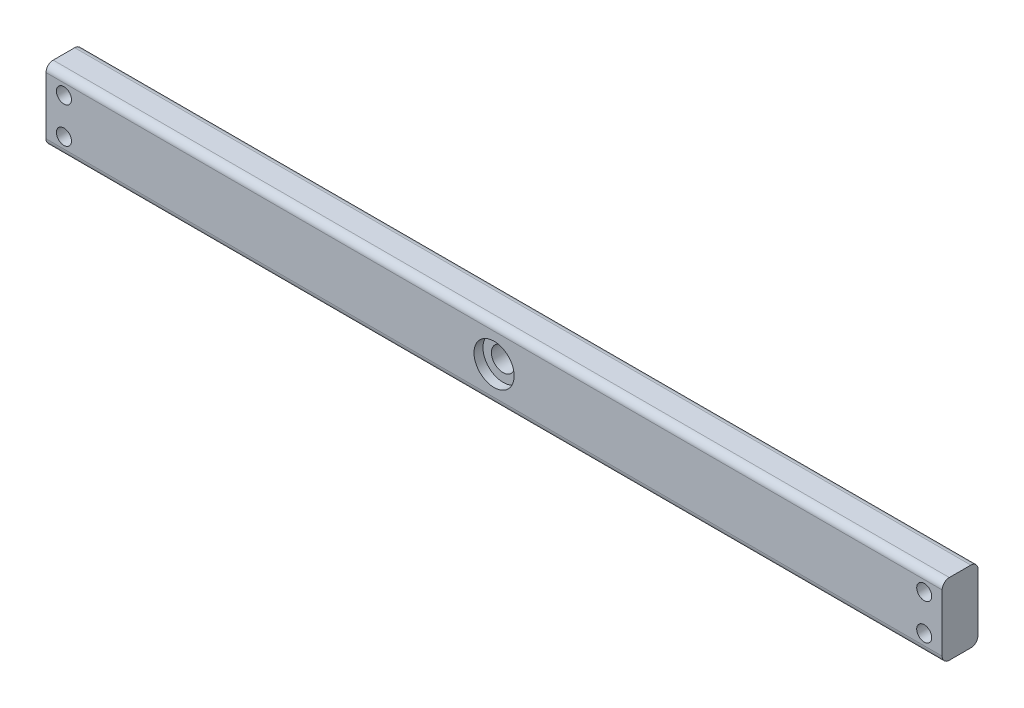
SolidWorks part; units mm, degrees
ref_plane "前视基准面" through (0, 0, 0) normal (0, 0, 1) x (1, 0, 0)
ref_plane "上视基准面" through (0, 0, 0) normal (0, 1, 0) x (1, 0, 0)
ref_plane "右视基准面" through (0, 0, 0) normal (1, 0, 0) x (0, 0, -1)
other "Configuration Table"
sketch "草图1" plane through (0, 0, 0) normal (0, 0, 1) x (1, 0, 0)
  line L1 (-125, 10) -> (125, 10)
  line L2 (-125, 10) -> (-125, -10)
  line L3 (-125, -10) -> (125, -10)
  line L4 (125, 10) -> (125, -10)
  line L5 (-125, 10) -> (125, -10) construction
  line L6 (-125, -10) -> (125, 10) construction
  circle A0 centre (0, 0) radius 3.25
  point P0 (0, 0)
  dimension "D1" = 6.5
  dimension "D2" = 250
  dimension "D3" = 20
extrude "凸台-拉伸1" add sketch "草图1" along normal mid plane 10
sketch "草图2" plane through (0, 0, -5) normal (0, 0, -1) x (-1, 0, 0)
  circle A0 centre (0, 0) radius 5.6
  dimension "D1" = 11.2
extrude "切除-拉伸1" cut sketch "草图2" against normal blind 2.5
sketch "草图3" plane through (0, 0, 5) normal (0, 0, 1) x (1, 0, 0)
  circle A0 centre (0, 0) radius 5.6
  dimension "D1" = 11.2
extrude "切除-拉伸2" cut sketch "草图3" against normal blind 2.5
sketch "草图4" plane through (0, 0, 5) normal (0, 0, 1) x (1, 0, 0)
  line L0 (125, 10) -> (-125, 10) construction
  line L1 (-125, 10) -> (-125, -10) construction
  line L2 (0, 0) -> (0, -55.5514) construction
  circle A0 centre (-120, 5) radius 2.1
  circle A1 centre (-120, -5) radius 2.1
  circle A2 centre (120, -5) radius 2.1
  circle A3 centre (120, 5) radius 2.1
  dimension "D1" = 4.2
  dimension "D2" = 10
  dimension "D3" = 5
  dimension "D4" = 5
extrude "切除-拉伸3" cut sketch "草图4" against normal through all
fillet "圆角1" radius 2 4 edges at (0, -10, -5) (0, -10, 5) (0, 10, -5) (0, 10, 5)
